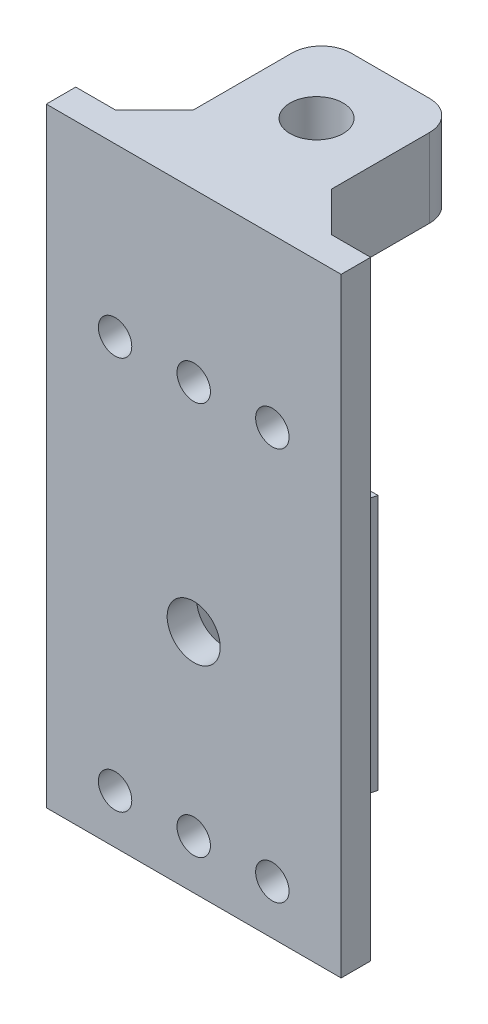
SolidWorks part; units mm, degrees
ref_plane "前视基准面" through (0, 0, 0) normal (0, 0, 1) x (1, 0, 0)
ref_plane "上视基准面" through (0, 0, 0) normal (0, 1, 0) x (1, 0, 0)
ref_plane "右视基准面" through (0, 0, 0) normal (1, 0, 0) x (0, 0, -1)
sketch "草图1" plane through (0, 0, 0) normal (0, 0, 1) x (1, 0, 0)
  line L0 (0, -1000) -> (0, 49000) construction
  line L1 (-15, -39) -> (15, -39) construction
  line L2 (-15, -39) -> (-15, 39)
  line L3 (-15, 39) -> (15, 39)
  line L4 (15, -39) -> (15, 39)
  line L5 (-15, -39) -> (15, 39) construction
  line L6 (-15, 39) -> (15, -39) construction
  line L7 (-15, -23) -> (15, -23)
  line L14 (-15, -27) -> (15, -27) construction
  line L15 (-15, -27) -> (-15, 27)
  line L16 (-15, 27) -> (15, 27) construction
  line L17 (15, -27) -> (15, 27)
  line L18 (-15, -27) -> (15, 27) construction
  line L19 (-15, 27) -> (15, -27) construction
  circle A0 centre (0, 22) radius 1.7
  circle A1 centre (8, 22) radius 1.7
  circle A2 centre (-8, 22) radius 1.7
  circle A3 centre (0, 0) radius 2.7
  circle A4 centre (-8, -18) radius 1.7
  circle A5 centre (0, -18) radius 1.7
  circle A6 centre (8, -18) radius 1.7
  point P0 (0, 0)
  point P19 (0, 0)
  dimension "D5" = 3.4
  dimension "D7" = 3.4
  dimension "D3" = 5.4
  dimension "D1" = 30
  dimension "D2" = 12
  dimension "D4" = 22
  dimension "D6" = 16
  dimension "D8" = 5
  dimension "D9" = 18
  dimension "D10" = 5
  dimension "D11" = 50
extrude "凸台-拉伸1" add sketch "草图1" along normal blind 3
sketch "草图3" plane through (0, 0, 0) normal (0, 0, -1) x (-1, 0, 0)
  line L0 (15, 39) -> (-15, 39) construction
  line L1 (-7, 31) -> (7, 31)
  line L2 (-7, 31) -> (-7, 39)
  line L3 (-7, 39) -> (7, 39)
  line L4 (7, 31) -> (7, 39)
  line L5 (-7, 31) -> (7, 39) construction
  line L6 (-7, 39) -> (7, 31) construction
  point P0 (0, 35)
  dimension "D1" = 14
  dimension "D2" = 8
extrude "凸台-拉伸2" add sketch "草图3" along normal blind 17
sketch "草图5" plane through (0, 31, 0) normal (0, -1, 0) x (1, 0, 0)
  line L1 (4, -11.8094) -> (4, -7.1906)
  line L2 (4, -7.1906) -> (0, -4.8812)
  line L3 (0, -4.8812) -> (-4, -7.1906)
  line L4 (-4, -7.1906) -> (-4, -11.8094)
  line L5 (-4, -11.8094) -> (0, -14.1188)
  line L6 (0, -14.1188) -> (4, -11.8094)
  line L7 (7, -17) -> (-7, -17) construction
  circle A0 centre (0, -9.5) radius 4 construction
  dimension "D1" = 8
  dimension "D2" = 7.5
extrude "切除-拉伸1" cut sketch "草图5" against normal blind 4
sketch "草图6" plane through (0, 35, 0) normal (0, -1, 0) x (1, 0, 0)
  line L1 (0, -4.8812) -> (-4, -7.1906) construction
  line L2 (-4, -7.1906) -> (-4, -11.8094) construction
  line L3 (-4, -11.8094) -> (0, -14.1188) construction
  line L4 (0, -14.1188) -> (4, -11.8094) construction
  line L5 (4, -11.8094) -> (4, -7.1906) construction
  line L6 (4, -7.1906) -> (0, -4.8812) construction
  circle A0 centre (0, -9.5) radius 2.7
  circle A1 centre (0, -9.5) radius 4 construction
  dimension "D1" = 5.4
extrude "切除-拉伸2" cut sketch "草图6" against normal up to next
fillet "圆角1" radius 3 2 edges at (-7, 35, -17) (7, 35, -17)
chamfer "倒角1" distance 4 angle 45 2 edges
sketch "草图7" plane through (0, 0, 0) normal (0, 0, -1) x (-1, 0, 0)
  line L0 (0, -1000) -> (0, 49000) construction
  line L1 (-11.45, -11) -> (-4.55, -11)
  line L2 (-11.45, -11) -> (-11.45, 15)
  line L3 (-11.45, 15) -> (-4.55, 15)
  line L4 (-4.55, -11) -> (-4.55, 15)
  line L5 (-11.45, -11) -> (-4.55, 15) construction
  line L6 (-11.45, 15) -> (-4.55, -11) construction
  line L7 (11.45, 15) -> (4.55, -11) construction
  line L8 (11.45, -11) -> (4.55, 15) construction
  line L9 (4.55, -11) -> (4.55, 15)
  line L10 (11.45, 15) -> (4.55, 15)
  line L11 (11.45, -11) -> (11.45, 15)
  line L12 (11.45, -11) -> (4.55, -11)
  circle A0 centre (-8, 22) radius 1.7 construction
  circle A1 centre (-8, -18) radius 1.7 construction
  circle A2 centre (-8, -18) radius 1.7 construction
  circle A3 centre (-8, 22) radius 1.7 construction
  point P0 (-8, 2)
  point P15 (8, 2)
  dimension "D1" = 6.9
  dimension "D2" = 7
  dimension "D3" = 7
extrude "凸台-拉伸3" add sketch "草图7" along normal blind 3.4
sketch "草图8" plane through (0, 15, 0) normal (0, 1, 0) x (1, 0, 0)
  line L0 (11.45, 0) -> (11.45, 3.4)
  line L1 (11.45, 3.4) -> (12.35, 3.4)
  line L3 (12.35, 3.4) -> (11.45, 0)
  line L4 (0, -1000) -> (0, 49000) construction
  line L5 (8, -996.6) -> (8, 49003.4) construction
  line L6 (11.45, 3.4) -> (4.55, 3.4) construction
  line L7 (3.65, 3.4) -> (4.55, 0)
  line L8 (4.55, 3.4) -> (3.65, 3.4)
  line L9 (4.55, 0) -> (4.55, 3.4)
  line L10 (-12.35, 3.4) -> (-11.45, 0)
  line L11 (-11.45, 3.4) -> (-12.35, 3.4)
  line L12 (-11.45, 0) -> (-11.45, 3.4)
  line L13 (-4.55, 0) -> (-4.55, 3.4)
  line L14 (-4.55, 3.4) -> (-3.65, 3.4)
  line L15 (-3.65, 3.4) -> (-4.55, 0)
  point P15 (8, 3.4)
  dimension "D1" = 0.9
extrude "凸台-拉伸4" add sketch "草图8" against normal up to surface (26 mm away) up to face at (8, -11, -1.7)
